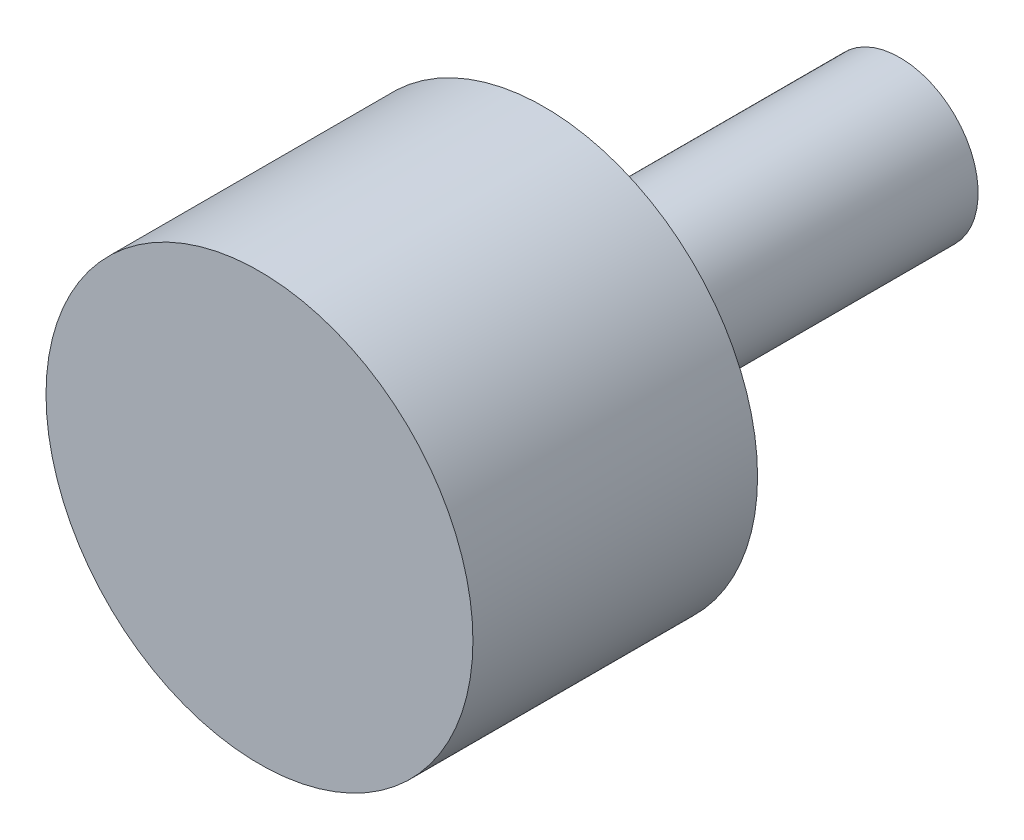
SolidWorks part; units mm, degrees
ref_plane "Front Plane" through (0, 0, 0) normal (0, 0, 1) x (1, 0, 0)
ref_plane "Top Plane" through (0, 0, 0) normal (0, 1, 0) x (1, 0, 0)
ref_plane "Right Plane" through (0, 0, 0) normal (1, 0, 0) x (0, 0, -1)
sketch "Sketch1" plane through (0, 0, 0) normal (0, 0, 1) x (1, 0, 0)
  circle A0 centre (0, 0) radius 15
  dimension "D1" = 30
extrude "Boss-Extrude1" add sketch "Sketch1" along normal blind 20
sketch "Sketch2" plane through (0, 0, 0) normal (0, 0, -1) x (-1, 0, 0)
  circle A0 centre (0, 0) radius 5.5
  dimension "D1" = 11
extrude "Boss-Extrude2" add sketch "Sketch2" along normal blind 25
